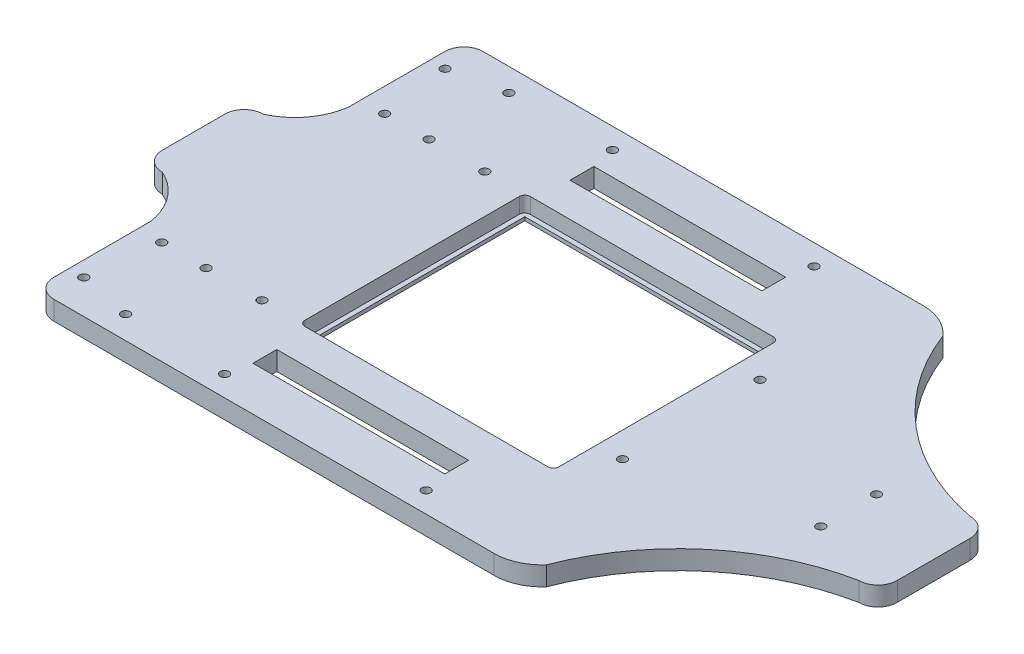
SolidWorks part; units mm, degrees
ref_plane "Alzado" through (0, 0, 0) normal (0, 0, 1) x (1, 0, 0)
ref_plane "Planta" through (0, 0, 0) normal (0, 1, 0) x (1, 0, 0)
ref_plane "Vista lateral" through (0, 0, 0) normal (1, 0, 0) x (0, 0, -1)
sketch "Croquis1" plane through (0, 0, 0) normal (0, 1, 0) x (1, 0, 0)
  line L1 (-363.842, 247.1559) -> (108.158, 247.1559) construction
  line L2 (98.4842, 266.9705) -> (494.4842, 266.9705) construction
  line L11 (99, 267.5) -> (495, 267.5) construction
  line L12 (0, 0) -> (200, 0)
  line L22 (0, 90) -> (105.7, 90)
  line L23 (105.7, 90) -> (105.7, 83.1308) construction
  line L24 (105.7, 83.1308) -> (120.7782, 83.1308) construction
  line L25 (200, 0) -> (200, 15.2)
  line L26 (200, 15.2) -> (191.999, 15.2) construction
  line L27 (191.999, 15.2) -> (191.999, 23.325) construction
  line L29 (0, 0) -> (-110.4, 0)
  line L30 (0, 90) -> (-79, 90)
  line L31 (-110.4, 0) -> (-110.4, 13.12)
  line L32 (-86.9998, 82.0528) -> (-86.9998, 41.494)
  arc A0 (105.7, 90) -> (120.7782, 83.1308) centre (105.672, 69.9553) cw
  arc A1 (200, 15.2) -> (191.999, 23.325) centre (192.001, 15.325) ccw
  arc A2 (120.7782, 83.1308) -> (191.999, 23.325) centre (210.4273, 117.5809) ccw
  arc A3 (-79, 90) -> (-86.9998, 82.0528) centre (-79, 82) ccw
  arc A4 (-110.4, 13.12) -> (-102.3535, 21.1199) centre (-102.4, 13.12) cw
  arc A5 (-102.3535, 21.1199) -> (-86.9998, 41.494) centre (-113.1395, 45.2203) ccw
  dimension "D6" = 20.0447
  dimension "D10" = 8
  dimension "D11" = 96.0405
  dimension "D15" = 8
  dimension "D17" = 8
  dimension "D19" = 26.4039
  dimension "D22" = 45.2203
  dimension "D1" = 90
  dimension "D2" = 200
  dimension "D3" = 105.7
  dimension "D4" = 6.8692
  dimension "D5" = 15.0782
  dimension "D7" = 15.2
  dimension "D8" = 8.001
  dimension "D9" = 8.125
  dimension "D12" = 105.7
  dimension "D13" = 310.4
  dimension "D14" = 79
  dimension "D16" = 13.12
  dimension "D18" = 40.5588
  dimension "D20" = 90
  dimension "D21" = 286.9998
extrude "Saliente-Extruir1" add sketch "Croquis1" along normal blind 8
mirror "Simetría2" about plane through (0, 8, 0) normal (0, 0, -1) of bodies 104
sketch "Croquis2" plane through (0, 8, 0) normal (0, 1, 0) x (1, 0, 0)
  line L0 (200, 0) -> (-110.4, 0) construction
  line L1 (200, -15.2) -> (200, 15.2) construction
  line L2 (-110.4, 13.12) -> (-110.4, -13.12) construction
  line L3 (0, 90) -> (-86.9348, 90) construction
  line L4 (105.7, 90) -> (-79, 90) construction
  line L8 (13.35, -90) -> (13.35, 90) construction
  line L9 (105.7, -90) -> (-79, -90) construction
  line L10 (-17.875, -81.35) -> (70.325, -81.35) construction
  line L11 (-14, -61.5) -> (66.45, -61.5)
  line L12 (-14, -61.5) -> (-14, -71.5)
  line L13 (-14, -71.5) -> (66.45, -71.5)
  line L14 (66.45, -61.5) -> (66.45, -71.5)
  line L15 (-14, 71.5) -> (66.45, 71.5)
  line L16 (66.45, 61.5) -> (66.45, 71.5)
  line L17 (-14, 61.5) -> (66.45, 61.5)
  line L18 (-14, 61.5) -> (-14, 71.5)
  line L19 (70.325, 81.35) -> (-17.875, 81.35) construction
  circle A0 centre (68.5, 81.35) radius 1.825
  circle A1 centre (-16.05, 81.35) radius 1.825
  circle A2 centre (68.5, -81.35) radius 1.825
  circle A3 centre (-16.05, -81.35) radius 1.825
  point P33 (26.225, -61.5)
  point P34 (26.225, -81.35)
  dimension "D1" = 3.65
  dimension "D5" = 3.65
  dimension "D10" = 84.55
  dimension "D2" = 81.35
  dimension "D3" = 110.4
  dimension "D4" = 68.5
  dimension "D6" = 88.2
  dimension "D7" = 80.45
  dimension "D8" = 10
  dimension "D9" = 18.5
extrude "Cortar-Extruir1" cut sketch "Croquis2" against normal through all
sketch "Croquis3" plane through (0, 8, 0) normal (0, 1, 0) x (1, 0, 0)
  line L0 (-86.9998, 41.494) -> (-86.9998, -41.494) construction
  line L1 (-110.4, 13.12) -> (-110.4, -13.12) construction
  line L2 (-110.4, 0) -> (200, 0) construction
  line L3 (200, -15.2) -> (200, 15.2) construction
  line L4 (-55.9998, 58.35) -> (-55.9998, -58.35) construction
  line L5 (-86.9998, 58.35) -> (-24.9998, 58.35) construction
  line L6 (-86.9998, 58.35) -> (-86.9998, -58.35) construction
  line L7 (-86.9998, -58.35) -> (-24.9998, -58.35) construction
  line L8 (-24.9998, 58.35) -> (-24.9998, -58.35) construction
  line L9 (-76.9998, -46.75) -> (-34.9998, -46.75) construction
  line L10 (-76.9998, 46.75) -> (-34.9998, 46.75) construction
  circle A0 centre (-76.9998, -46.75) radius 1.825
  circle A1 centre (-34.9998, -46.75) radius 1.825
  circle A2 centre (-34.9998, 46.75) radius 1.825
  circle A3 centre (-76.9998, 46.75) radius 1.825
  point P14 (-86.9998, 0)
  point P15 (-86.9998, 0)
  point P22 (-55.9998, -46.75)
  dimension "D4" = 3.65
  dimension "D5" = 3.65
  dimension "D1" = 23.4002
  dimension "D2" = 116.7
  dimension "D3" = 62
  dimension "D6" = 42
  dimension "D7" = 93.5
extrude "Cortar-Extruir2" cut sketch "Croquis3" against normal through all
sketch "Croquis4" plane through (0, 8, 0) normal (0, 1, 0) x (1, 0, 0)
  line L0 (-110.4, 0) -> (200, 0) construction
  line L1 (-110.4, 13.12) -> (-110.4, -13.12) construction
  line L2 (200, -15.2) -> (200, 15.2) construction
  line L3 (34.5252, 61.5) -> (34.5252, -61.5) construction
  line L4 (87.7752, 47.25) -> (-18.7248, 47.25)
  line L5 (87.7752, 47.25) -> (87.7752, -47.25)
  line L6 (87.7752, -47.25) -> (-18.7248, -47.25)
  line L7 (-18.7248, 47.25) -> (-18.7248, -47.25)
  line L10 (-33.1748, 46.75) -> (-24.8248, 46.75) construction
  circle A0 centre (-34.9998, 46.75) radius 1.825 construction
  point P10 (87.7752, 0)
  point P17 (34.5252, 47.25)
  dimension "D1" = 106.5
  dimension "D2" = 94.5
  dimension "D3" = 8.35
  dimension "D4" = 59.35
extrude "Cortar-Extruir3" cut sketch "Croquis4" against normal blind 6.5
fillet "Redondeo1" radius 2.3 4 edges at (-18.7248, 4.75, -47.25) (87.7752, 4.75, 47.25) (87.7752, 4.75, -47.25) (-18.7248, 4.75, 47.25)
sketch "Croquis5" plane through (0, 8, 0) normal (0, 1, 0) x (1, 0, 0)
  line L0 (200, 0) -> (-110.4, 0) construction
  line L1 (200, -15.2) -> (200, 15.2) construction
  line L2 (-110.4, 13.12) -> (-110.4, -13.12) construction
  line L3 (150, 85.1406) -> (150, -85.1406) construction
  line L4 (112.7, 87.625) -> (112.7, -87.625) construction
  line L5 (150, 85.1406) -> (112.7, 87.625) construction
  line L6 (150, -85.1406) -> (112.7, -87.625) construction
  line L7 (154, 57.685) -> (154, -57.685) construction
  line L8 (108.7, -57.685) -> (108.7, 57.685) construction
  line L9 (154, 57.685) -> (108.7, 57.685) construction
  line L10 (154, -57.685) -> (108.7, -57.685) construction
  line L11 (87.7752, -44.95) -> (87.7752, 44.95) construction
  line L12 (108.7, 33.49) -> (93.7, 33.49) construction
  line L13 (108.7, 33.49) -> (108.7, 24.19) construction
  line L14 (108.7, 24.19) -> (93.7, 24.19) construction
  line L15 (93.7, 33.49) -> (93.7, 24.19) construction
  line L16 (-18.7248, 44.95) -> (-18.7248, 48.2965) construction
  line L17 (-33.1748, 46.75) -> (-18.7248, 46.75) construction
  line L18 (-24.8248, 46.75) -> (-24.8248, 0) construction
  line L19 (93.7, 28.84) -> (108.7, 28.84) construction
  line L20 (-86.9998, 82.0528) -> (-86.9998, 41.494) construction
  line L21 (191.999, 23.325) -> (154, 23.325) construction
  line L22 (169, 11.66) -> (154, 11.66) construction
  line L23 (154, 16.31) -> (169, 16.31) construction
  line L24 (154, 16.31) -> (154, 7.01) construction
  line L25 (154, 7.01) -> (169, 7.01) construction
  line L26 (169, 16.31) -> (169, 7.01) construction
  circle A0 centre (-34.9998, 46.75) radius 1.825 construction
  circle A1 centre (98.35, 28.84) radius 1.825
  circle A2 centre (98.35, -28.84) radius 1.825
  circle A3 centre (164.35, 11.66) radius 1.825
  circle A4 centre (164.35, -11.66) radius 1.825
  point P8 (150, 0)
  point P11 (112.7, 0)
  point P14 (154, 0)
  point P18 (108.7, 0)
  point P22 (93.7, 28.84)
  point P50 (169, 11.66)
  dimension "D15" = 3.65
  dimension "D23" = 3.65
  dimension "D1" = 50
  dimension "D2" = 170.2811
  dimension "D3" = 37.3
  dimension "D4" = 175.25
  dimension "D5" = 115.37
  dimension "D6" = 115.37
  dimension "D7" = 4
  dimension "D8" = 4
  dimension "D9" = 28.845
  dimension "D10" = 4.65
  dimension "D11" = 15
  dimension "D12" = 5.9248
  dimension "D13" = 14.45
  dimension "D14" = 8.35
  dimension "D16" = 4.65
  dimension "D17" = 118.5248
  dimension "D18" = 62.175
  dimension "D19" = 23.325
  dimension "D20" = 11.66
  dimension "D21" = 4.65
  dimension "D22" = 15
  dimension "D24" = 4.65
extrude "Cortar-Extruir4" cut sketch "Croquis5" against normal through all
sketch "Croquis6" plane through (0, 1.5, 0) normal (0, 1, 0) x (1, 0, 0)
  line L0 (85.4752, 47.25) -> (-16.4248, 47.25) construction
  line L1 (-16.7248, 45.25) -> (85.7752, 45.25)
  line L2 (-16.7248, 45.25) -> (-16.7248, -45.25)
  line L3 (-16.7248, -45.25) -> (85.7752, -45.25)
  line L4 (85.7752, 45.25) -> (85.7752, -45.25)
  line L5 (-18.7248, 44.95) -> (-18.7248, -44.95) construction
  point P6 (34.5252, 47.25)
  point P7 (34.5252, 45.25)
  point P10 (-18.7248, 0)
  point P11 (-16.7248, 0)
  dimension "D1" = 2
  dimension "D2" = 2
extrude "Cortar-Extruir5" cut sketch "Croquis6" against normal through all
sketch "Croquis7" plane through (0, 8, 0) normal (0, 1, 0) x (1, 0, 0)
  line L0 (-9.7248, -28.75) -> (-48.4, -28.75) construction
  line L1 (-48.4, -53.35) -> (-48.4, 53.35) construction
  line L2 (-16.7248, 45.25) -> (-16.7248, -45.25) construction
  line L4 (-16.7248, -24.7566) -> (-16.7248, -27.7566) construction
  line L5 (-38.8, -28.75) -> (-48.4, -28.75) construction
  line L6 (34.5252, 47.25) -> (34.5252, -47.25) construction
  line L7 (85.4752, 47.25) -> (-16.4248, 47.25) construction
  line L8 (-16.4248, -47.25) -> (85.4752, -47.25) construction
  line L9 (-9.7248, 29.25) -> (-18.5248, 29.25) construction
  line L10 (98.375, 27.1852) -> (98.375, 34.1852) construction
  line L11 (76.2752, 29.25) -> (98.375, 29.25) construction
  line L12 (87.7752, 32.25) -> (87.7752, 29.25) construction
  line L13 (87.7752, -44.95) -> (87.7752, 44.95) construction
  line L14 (76.2752, -28.75) -> (93.0752, -28.75) construction
  circle A0 centre (-9.7248, -28.75) radius 2 construction
  circle A1 centre (-43.6, -28.75) radius 1.65
  circle A2 centre (-9.7248, 29.25) radius 2 construction
  circle A3 centre (-18.5248, 29.25) radius 1.65
  circle A4 centre (98.35, 28.835) radius 1.65 construction
  circle A5 centre (76.2752, 29.25) radius 2 construction
  circle A6 centre (93.0752, 29.25) radius 1.65
  circle A7 centre (76.2752, -28.75) radius 2 construction
  circle A8 centre (93.0752, -28.75) radius 1.65
  point P10 (-18.1606, -28.75)
  dimension "D1" = 4
  dimension "D5" = 3.3
  dimension "D6" = 4
  dimension "D9" = 3.3
  dimension "D10" = 4
  dimension "D13" = 3.3
  dimension "D18" = 4
  dimension "D20" = 3.3
  dimension "D2" = 3
  dimension "D3" = 9.6
  dimension "D4" = 4.8
  dimension "D7" = 33.8752
  dimension "D8" = 8.8
  dimension "D11" = 10.5998
  dimension "D12" = 5.3
  dimension "D14" = 3
  dimension "D15" = 7
  dimension "D16" = 1.4358
  dimension "D17" = 16.8
  dimension "D19" = 16.8
sketch "Croquis9" plane through (0, 8, 0) normal (0, 1, 0) x (1, 0, 0)
  line L0 (-110.4, 0) -> (200, 0) construction
  line L1 (-110.4, 13.12) -> (-110.4, -13.12) construction
  line L2 (200, -15.2) -> (200, 15.2) construction
  line L3 (-86.9998, -82.0528) -> (-86.9998, -41.494) construction
  line L4 (105.7, -90) -> (-79, -90) construction
  circle A0 centre (-80.6754, -75.7672) radius 1.825
  circle A1 centre (-58.5237, -80.3706) radius 1.825
  circle A2 centre (-58.5237, 80.3706) radius 1.825
  circle A3 centre (-80.6754, 75.7672) radius 1.825
  dimension "D3" = 3.65
  dimension "D4" = 3.65
  dimension "D1" = 6.3244
  dimension "D2" = 14.2328
  dimension "D5" = 9.6294
  dimension "D6" = 28.4762
extrude "Cortar-Extruir7" cut sketch "Croquis9" against normal through all
sketch "Croquis10" plane through (0, 8, 0) normal (0, 1, 0) x (1, 0, 0)
  line L0 (66.675, 81.35) -> (-14.225, 81.35) construction
  line L1 (-17.875, 81.35) -> (70.325, 81.35) construction
  circle A0 centre (68.5, 81.35) radius 1.825 construction
  circle A1 centre (-16.05, 81.35) radius 1.825 construction
  dimension "D1" = 80.9
  dimension "D2" = 80.9
  dimension "D3" = 88.2
sketch "Croquis11" plane through (0, 8, 0) normal (0, 1, 0) x (1, 0, 0)
  line L0 (-110.4, 0) -> (-30.6357, 0) construction
  line L1 (-110.4, 53.35) -> (-110.4, -53.35) construction
  circle A0 centre (-58.4, 46.75) radius 1.825
  circle A1 centre (-58.4, -46.75) radius 1.825
  dimension "D1" = 3.65
extrude "Cortar-Extruir8" cut sketch "Croquis11" against normal through all
